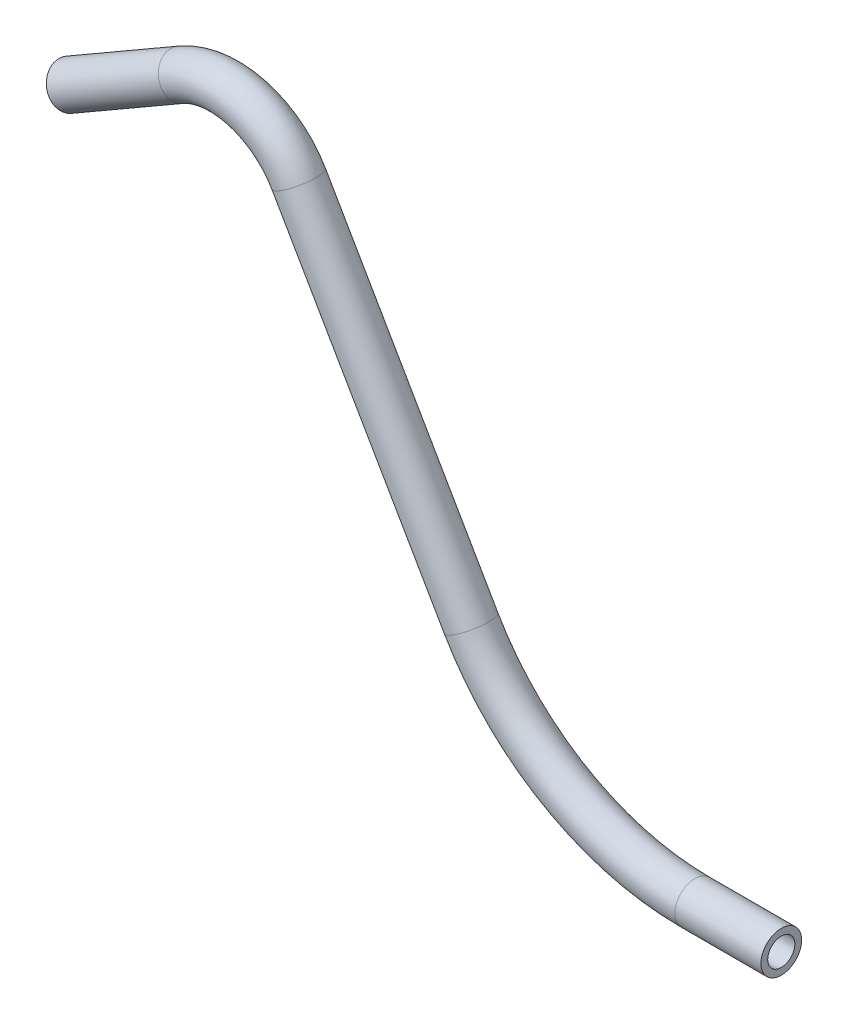
SolidWorks part; units mm, degrees
ref_plane "Front Plane" through (0, 0, 0) normal (0, 0, 1) x (1, 0, 0)
ref_plane "Top Plane" through (0, 0, 0) normal (0, 1, 0) x (1, 0, 0)
ref_plane "Right Plane" through (0, 0, 0) normal (1, 0, 0) x (0, 0, -1)
sketch "Sketch1" plane through (0, 0, 0) normal (1, 0, 0) x (0, 0, -1)
  circle A0 centre (0, 0) radius 3
  circle A1 centre (0, 0) radius 2
  dimension "D1" = 4
  dimension "D2" = 1
sketch "Sketch2" plane through (0, 0, 0) normal (0, 0, 1) x (1, 0, 0)
  line L0 (0, 0) -> (-12.7, 0)
  line L1 (-88.4441, 67.6926) -> (-104.9419, 58.1676)
  line L2 (-45.6956, 19.05) -> (-71.0956, 63.0441)
  arc A0 (-12.7, 0) -> (-45.6956, 19.05) centre (-12.7, 38.1) cw
  arc A1 (-71.0956, 63.0441) -> (-88.4441, 67.6926) centre (-82.0941, 56.6941) ccw
  point P9 (-58.3956, 41.047)
  dimension "D6" = 38.1
  dimension "D7" = 12.7
  dimension "D1" = 12.7
  dimension "D2" = 69.3941
  dimension "D3" = 50.8
  dimension "D4" = 60
  dimension "D5" = 104.9419
  dimension "D8" = 19.05
  dimension "D9" = 90
sweep "Sweep1" add profiles "Sketch1" path "Sketch2"
